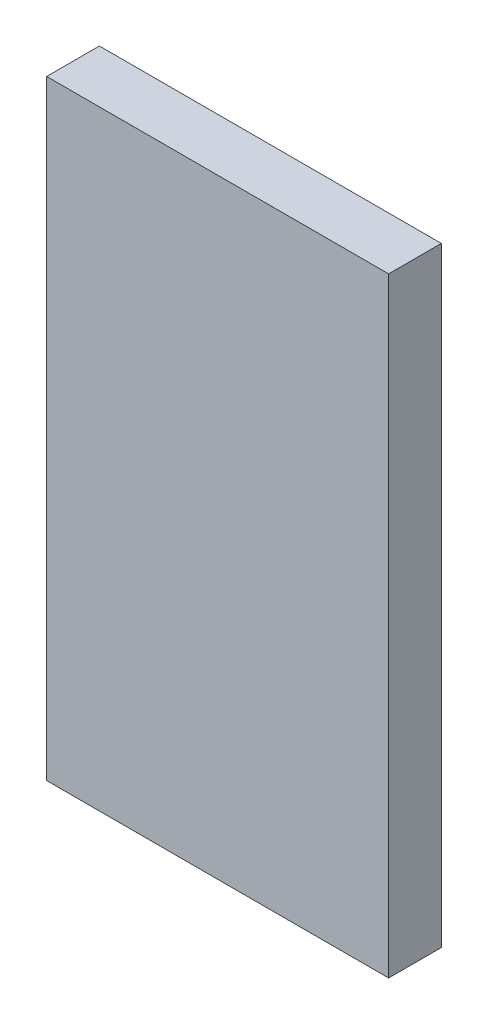
SolidWorks part; units mm, degrees
ref_plane "Front Plane" through (0, 0, 0) normal (0, 0, 1) x (1, 0, 0)
ref_plane "Top Plane" through (0, 0, 0) normal (0, 1, 0) x (1, 0, 0)
ref_plane "Right Plane" through (0, 0, 0) normal (1, 0, 0) x (0, 0, -1)
ref_plane "Plane4" through (0, 0, 9.25) normal (0, 0, 1) x (1, 0, 0)
sketch "Sketch1" plane through (0, 0, 9.25) normal (0, 0, 1) x (1, 0, 0)
  line L0 (-30, 53.5) -> (-30, -53.5)
  line L1 (-30, -53.5) -> (30, -53.5)
  line L2 (30, -53.5) -> (30, 53.5)
  line L3 (30, 53.5) -> (-30, 53.5)
  dimension "D1" = 30
  dimension "D2" = 30
  dimension "D3" = 53.5
  dimension "D4" = 53.5
extrude "Boss-Extrude1" add sketch "Sketch1" against normal blind 9.25
